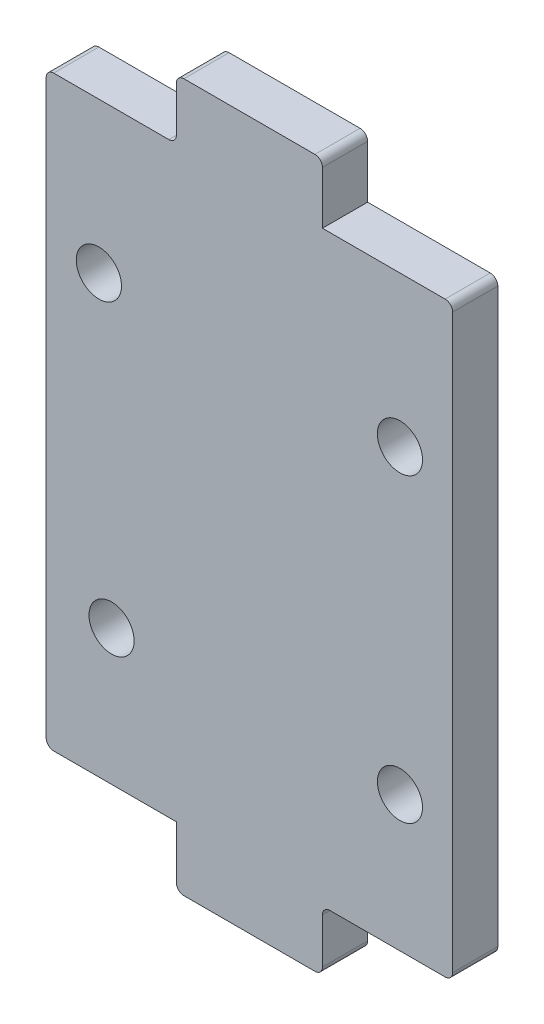
SolidWorks part; units mm, degrees
ref_plane "Plan de face" through (0, 0, 0) normal (0, 0, 1) x (1, 0, 0)
ref_plane "Plan de dessus" through (0, 0, 0) normal (0, 1, 0) x (1, 0, 0)
ref_plane "Plan de droite" through (0, 0, 0) normal (1, 0, 0) x (0, 0, -1)
sketch "Esquisse1" plane through (0, 0, 0) normal (0, 0, 1) x (1, 0, 0)
  line L1 (-13.5, 19.5) -> (-4.8513, 19.5)
  line L2 (-4.8513, 19.5) -> (-4.8513, 23.5)
  line L3 (-4.8513, 23.5) -> (4.8513, 23.5)
  line L4 (4.8513, 23.5) -> (4.8513, 19.5)
  line L5 (4.8513, 19.5) -> (13.5, 19.5)
  line L7 (27.1877, 0) -> (-29.8837, 0) construction
  line L8 (13.5, 19.5) -> (13.5, -19.5)
  line L22 (4.8513, -19.5) -> (13.5, -19.5)
  line L23 (4.8513, -23.5) -> (4.8513, -19.5)
  line L24 (-4.8513, -23.5) -> (4.8513, -23.5)
  line L25 (-4.8513, -19.5) -> (-4.8513, -23.5)
  line L34 (0, 42.283) -> (0, -38.676) construction
  line L35 (-13.5, 19.5) -> (-13.5, -19.5)
  line L36 (-4.8513, -19.5) -> (-13.5, -19.5)
  circle A0 centre (-10, 9.5) radius 1.5
  circle A1 centre (10, 9.5) radius 1.5
  circle A6 centre (-9.1585, -10.5) radius 1.5
  circle A7 centre (10, -10.5) radius 1.5
  point P0 (0, 23.5)
  point P11 (4.8513, 21.5)
  point P20 (13.5, 0)
  point P21 (4.8513, -21.5)
  dimension "D5" = 3
  dimension "D15" = 3
  dimension "D16" = 3
  dimension "D3" = 4
  dimension "D4" = 4
  dimension "D6" = 14
  dimension "D7" = 4
  dimension "D17" = 20
  dimension "D18" = 9.7027
extrude "Boss.-Extru.1" add sketch "Esquisse1" along normal blind 3
ref_plane "Plan1" through (0, 0, 0) normal (0, 1, 0) x (1, 0, 0)
fillet "Congé1" radius 0.5 10 edges at (-4.8513, -23.5, 1.5) (4.8513, -23.5, 1.5) (4.8513, -19.5, 1.5) (13.5, -19.5, 1.5) (13.5, 19.5, 1.5) (-4.8513, 19.5, 1.5) (4.8513, 23.5, 1.5) (-4.8513, 23.5, 1.5) (-13.5, 19.5, 1.5) (-13.5, -19.5, 1.5)
